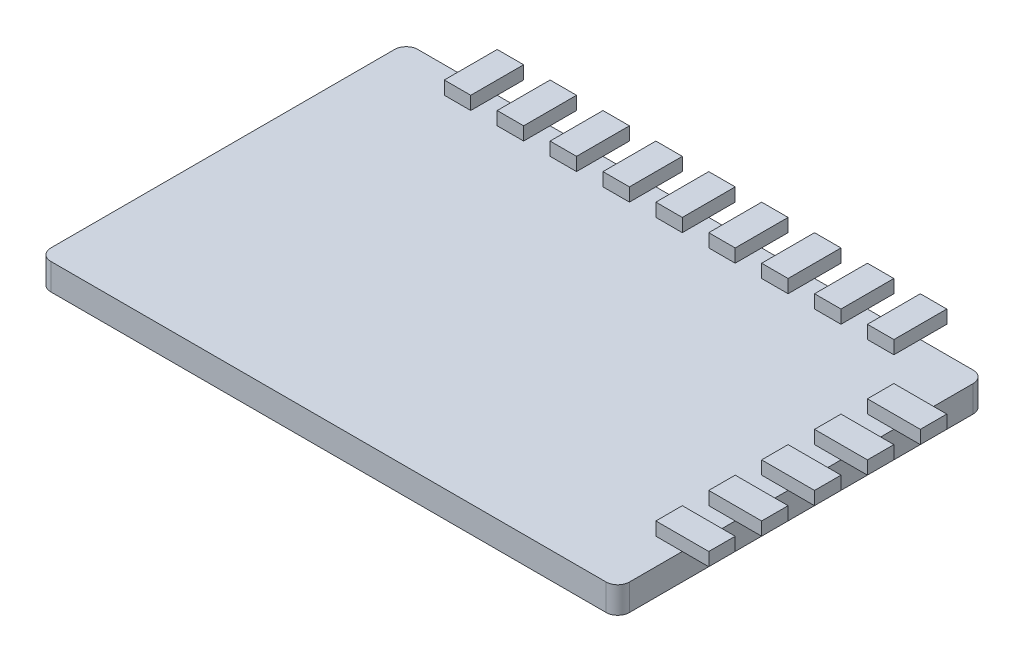
SolidWorks part; units mm, degrees
ref_plane "Front Plane" through (0, 0, 0) normal (0, 0, 1) x (1, 0, 0)
ref_plane "Top Plane" through (0, 0, 0) normal (0, 1, 0) x (1, 0, 0)
ref_plane "Right Plane" through (0, 0, 0) normal (1, 0, 0) x (0, 0, -1)
sketch "Sketch1" plane through (0, 0, 0) normal (0, 1, 0) x (-1, 0, 0)
  line L4 (145.669, -92.075) -> (145.669, -9.525)
  line L5 (142.875, -6.731) -> (9.525, -6.731)
  line L6 (6.731, -9.525) -> (6.731, -92.075)
  line L7 (9.525, -94.869) -> (142.875, -94.869)
  arc A4 (142.875, -6.731) -> (145.669, -9.525) centre (142.875, -9.525) cw
  arc A5 (9.525, -6.731) -> (6.731, -9.525) centre (9.525, -9.525) ccw
  arc A6 (6.731, -92.075) -> (9.525, -94.869) centre (9.525, -92.075) ccw
  arc A7 (142.875, -94.869) -> (145.669, -92.075) centre (142.875, -92.075) ccw
extrude "Boss-Extrude1" add sketch "Sketch1" along normal blind 6.35 contours L4 A4 L5 A5 L6 A6 L7 A7
sketch "Sketch2" plane through (0, 6.35, 0) normal (0, 1, 0) x (1, 0, 0)
  line L0 (-66.675, 88.519) -> (-60.325, 88.519)
  line L2 (-66.675, 88.519) -> (-66.675, 101.219)
  line L3 (-79.375, 88.519) -> (-73.025, 88.519)
  line L4 (-79.375, 88.519) -> (-79.375, 101.219)
  line L5 (-79.375, 101.219) -> (-73.025, 101.219)
  line L6 (-73.025, 101.219) -> (-73.025, 88.519)
  line L7 (-66.675, 101.219) -> (-60.325, 101.219)
  line L8 (-60.325, 101.219) -> (-60.325, 88.519)
  line L9 (-53.975, 88.519) -> (-47.625, 88.519)
  line L10 (-53.975, 88.519) -> (-53.975, 101.219)
  line L11 (-53.975, 101.219) -> (-47.625, 101.219)
  line L12 (-47.625, 101.219) -> (-47.625, 88.519)
  line L13 (-41.275, 88.519) -> (-34.925, 88.519)
  line L14 (-41.275, 88.519) -> (-41.275, 101.219)
  line L15 (-41.275, 101.219) -> (-34.925, 101.219)
  line L16 (-34.925, 101.219) -> (-34.925, 88.519)
  line L17 (-28.575, 88.519) -> (-22.225, 88.519)
  line L18 (-28.575, 88.519) -> (-28.575, 101.219)
  line L19 (-28.575, 101.219) -> (-22.225, 101.219)
  line L20 (-22.225, 101.219) -> (-22.225, 88.519)
  line L21 (-92.075, 88.519) -> (-85.725, 88.519)
  line L22 (-92.075, 88.519) -> (-92.075, 101.219)
  line L23 (-92.075, 101.219) -> (-85.725, 101.219)
  line L24 (-85.725, 101.219) -> (-85.725, 88.519)
  line L25 (-104.775, 88.519) -> (-98.425, 88.519)
  line L26 (-104.775, 88.519) -> (-104.775, 101.219)
  line L27 (-104.775, 101.219) -> (-98.425, 101.219)
  line L28 (-98.425, 101.219) -> (-98.425, 88.519)
  line L29 (-117.475, 88.519) -> (-111.125, 88.519)
  line L30 (-117.475, 88.519) -> (-117.475, 101.219)
  line L31 (-117.475, 101.219) -> (-111.125, 101.219)
  line L32 (-111.125, 101.219) -> (-111.125, 88.519)
  line L33 (-130.175, 88.519) -> (-123.825, 88.519)
  line L34 (-130.175, 88.519) -> (-130.175, 101.219)
  line L35 (-130.175, 101.219) -> (-123.825, 101.219)
  line L36 (-123.825, 101.219) -> (-123.825, 88.519)
  line L37 (-79.375, 94.869) -> (-73.025, 94.869)
  line L38 (-0.381, 47.625) -> (-0.381, 53.975)
  line L39 (-0.381, 47.625) -> (-13.081, 47.625)
  line L40 (-13.081, 47.625) -> (-13.081, 53.975)
  line L41 (-13.081, 53.975) -> (-0.381, 53.975)
  line L42 (-0.381, 60.325) -> (-0.381, 66.675)
  line L43 (-0.381, 60.325) -> (-13.081, 60.325)
  line L44 (-13.081, 60.325) -> (-13.081, 66.675)
  line L45 (-13.081, 66.675) -> (-0.381, 66.675)
  line L46 (-0.381, 73.025) -> (-0.381, 79.375)
  line L47 (-0.381, 73.025) -> (-13.081, 73.025)
  line L48 (-13.081, 73.025) -> (-13.081, 79.375)
  line L49 (-13.081, 79.375) -> (-0.381, 79.375)
  line L50 (-0.381, 34.925) -> (-0.381, 41.275)
  line L51 (-0.381, 34.925) -> (-13.081, 34.925)
  line L52 (-13.081, 34.925) -> (-13.081, 41.275)
  line L53 (-13.081, 41.275) -> (-0.381, 41.275)
  line L54 (-0.381, 22.225) -> (-0.381, 28.575)
  line L55 (-0.381, 22.225) -> (-13.081, 22.225)
  line L56 (-13.081, 22.225) -> (-13.081, 28.575)
  line L57 (-13.081, 28.575) -> (-0.381, 28.575)
  dimension "D1" = 5
  dimension "D2" = 5
  dimension "D3" = 3
  dimension "D4" = 3
extrude "Boss-Extrude2" add sketch "Sketch2" along normal blind 3.175 separate body contours L36 L33 L34 L35 | L32 L29 L30 L31 | L28 L25 L26 L27 | L24 L21 L22 L23 | L6 L3 L4 L5 | L8 L0 L2 L7 | L12 L9 L10 L11 | L16 L13 L14 L15 | L20 L17 L18 L19 | L47 L48 L49 L46 | L43 L44 L45 L42 | L41 L38 L39 L40 | L53 L50 L51 L52 | L57 L54 L55 L56
